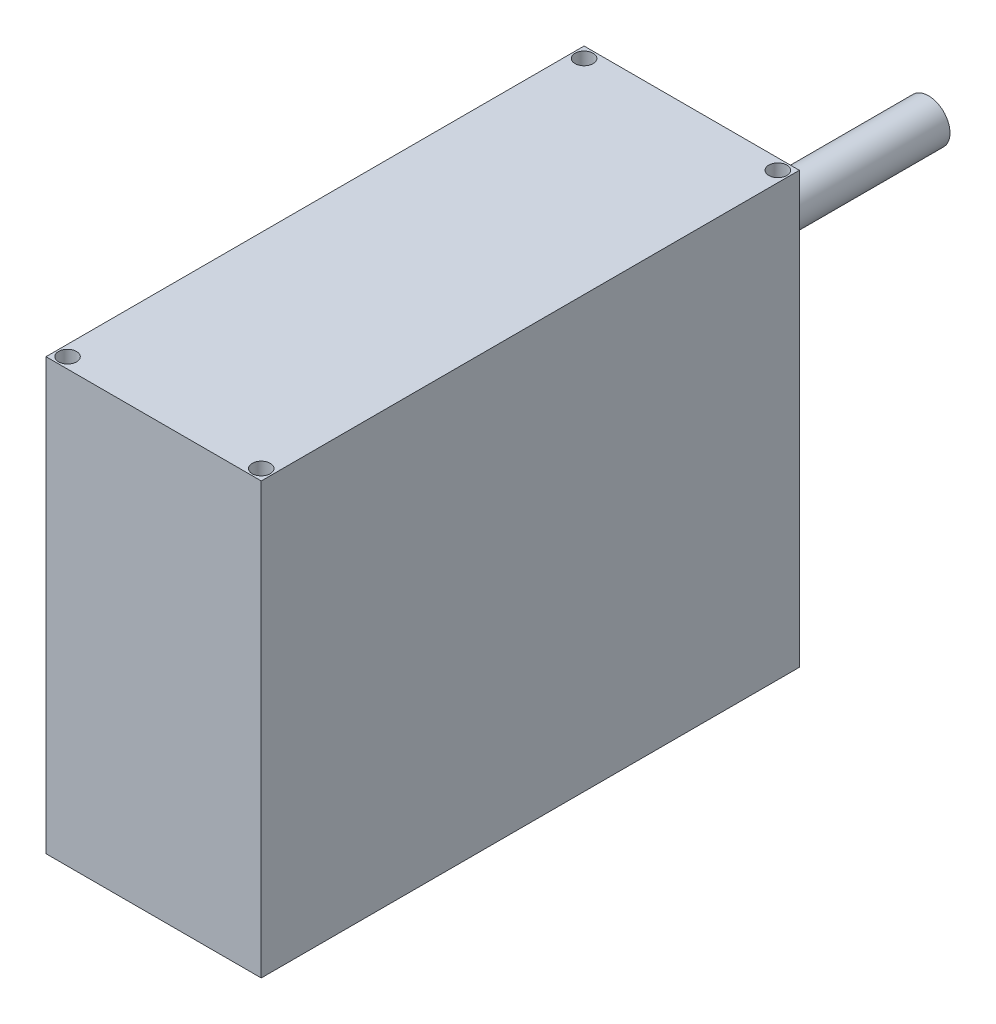
SolidWorks part; units mm, degrees
ref_plane "Front Plane" through (0, 0, 0) normal (0, 0, 1) x (1, 0, 0)
ref_plane "Top Plane" through (0, 0, 0) normal (0, 1, 0) x (1, 0, 0)
ref_plane "Right Plane" through (0, 0, 0) normal (1, 0, 0) x (0, 0, -1)
sketch "Sketch1" plane through (0, 0, 0) normal (0, 0, 1) x (1, 0, 0)
  line L1 (-25, -50) -> (25, -50)
  line L2 (-25, -50) -> (-25, 50)
  line L3 (-25, 50) -> (25, 50)
  line L4 (25, -50) -> (25, 50)
  line L5 (-25, -50) -> (25, 50) construction
  line L6 (-25, 50) -> (25, -50) construction
  point P0 (0, 0)
  dimension "D1" = 50
  dimension "D2" = 100
extrude "Boss-Extrude1" add sketch "Sketch1" along normal blind 125
sketch "Sketch2" plane through (0, 0, 0) normal (0, 0, 1) x (1, 0, 0)
  line L0 (25, 50) -> (-25, 50) construction
  circle A0 centre (0, 20) radius 5
  dimension "D1" = 10
  dimension "D2" = 30
extrude "Boss-Extrude2" add sketch "Sketch2" against normal blind 55
sketch "Sketch3" plane through (0, 50, 0) normal (0, 1, 0) x (1, 0, 0)
  line L0 (25, 0) -> (-25, 0) construction
  line L1 (-25, -125) -> (-25, 0) construction
  circle A0 centre (-22.5, -2.5) radius 2.1
  circle A1 centre (22.5, -2.5) radius 2.1
  circle A2 centre (22.5, -122.5) radius 2.1
  circle A3 centre (-22.5, -122.5) radius 2.1
  dimension "D1" = 4.2
  dimension "D2" = 2.5
  dimension "D3" = 2.5
  dimension "D4" = 2
  dimension "D5" = 2
extrude "Cut-Extrude1" cut sketch "Sketch3" against normal blind 6
sketch "Sketch4" plane through (0, 0, -55) normal (0, 0, -1) x (-1, 0, 0)
  circle A0 centre (0, 20) radius 3.2
  dimension "D1" = 6.4
extrude "Cut-Extrude2" cut sketch "Sketch4" against normal blind 10
